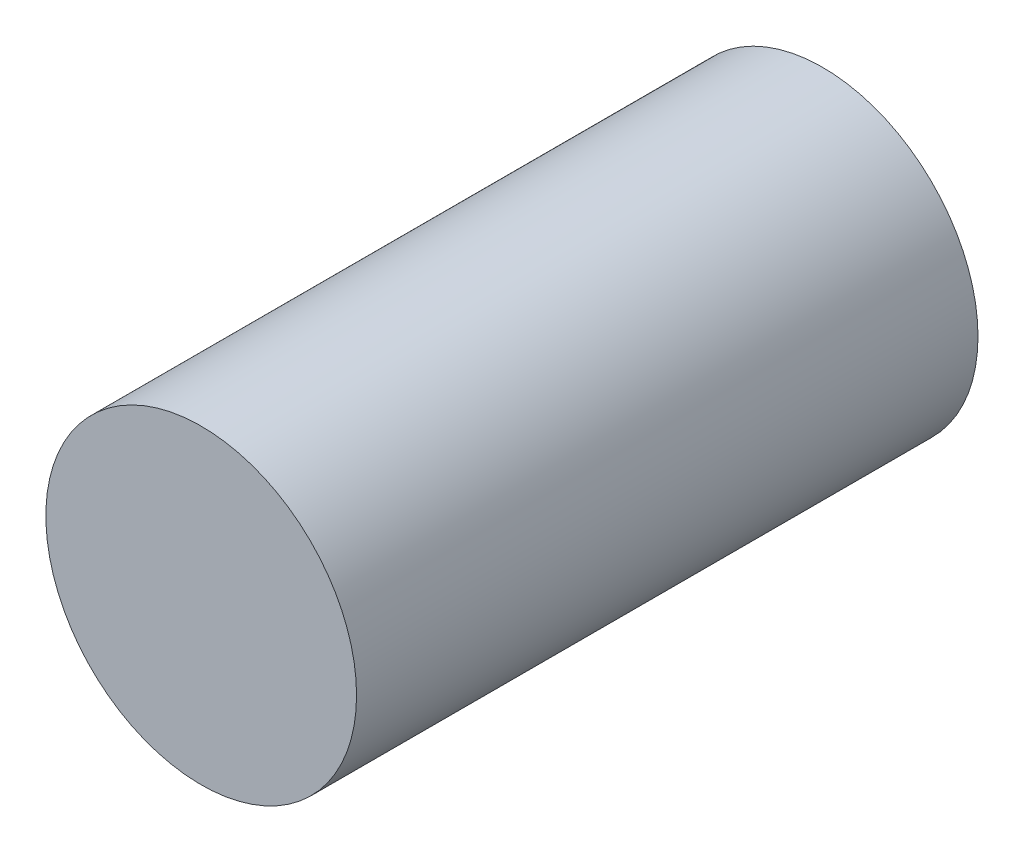
SolidWorks part; units mm, degrees
ref_plane "Спереди" through (0, 0, 0) normal (0, 0, 1) x (1, 0, 0)
ref_plane "Сверху" through (0, 0, 0) normal (0, 1, 0) x (1, 0, 0)
ref_plane "Справа" through (0, 0, 0) normal (1, 0, 0) x (0, 0, -1)
sketch "Эскиз1" plane through (0, 0, 0) normal (0, 0, 1) x (1, 0, 0)
  circle A0 centre (0, 0) radius 25
  dimension "D1" = 50
extrude "Бобышка-Вытянуть1" add sketch "Эскиз1" along normal blind 100
